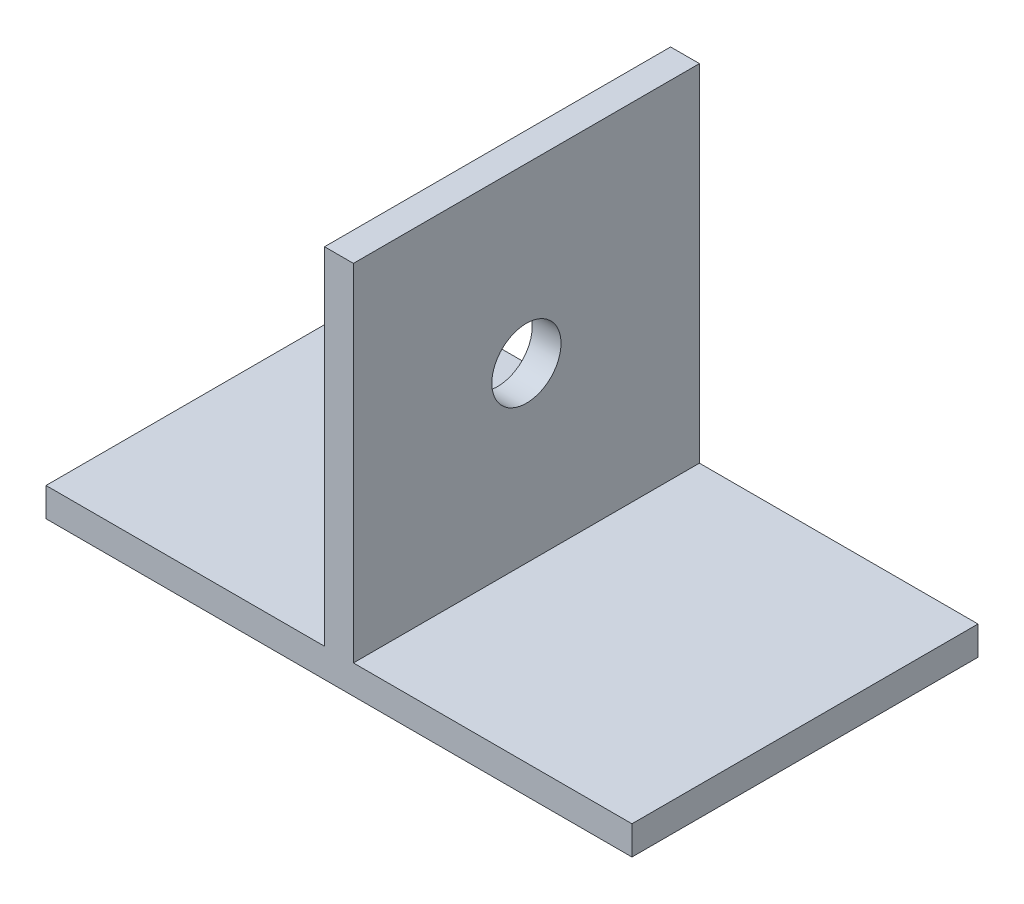
SolidWorks part; units mm, degrees
ref_plane "Front" through (0, 0, 0) normal (0, 0, 1) x (1, 0, 0)
ref_plane "Top" through (0, 0, 0) normal (0, 1, 0) x (1, 0, 0)
ref_plane "Right" through (0, 0, 0) normal (1, 0, 0) x (0, 0, -1)
sketch "草图1" plane through (0, 0, 0) normal (0, 0, 1) x (1, 0, 0)
  line L0 (0, 0) -> (0, -23.8891) construction
  line L1 (25.4, 0) -> (-25.4, 0)
  line L2 (-25.4, 0) -> (-25.4, 2.5)
  line L3 (-25.4, 2.5) -> (-1.25, 2.5)
  line L4 (-1.25, 2.5) -> (-1.25, 32.5)
  line L5 (-1.25, 32.5) -> (1.25, 32.5)
  line L6 (25.4, 0) -> (25.4, 2.5)
  line L7 (25.4, 2.5) -> (1.25, 2.5)
  line L8 (1.25, 2.5) -> (1.25, 32.5)
  point P8 (0, 32.5)
  point P12 (0, 0)
  dimension "D1" = 25.4
  dimension "D2" = 2.5
  dimension "D3" = 1.25
  dimension "D4" = 30
extrude "凸台-拉伸1" add sketch "草图1" along normal blind 30
sketch "草图2" plane through (1.25, 0, 0) normal (1, 0, 0) x (0, 0, -1)
  line L0 (-30, 2.5) -> (-30, 32.5) construction
  line L1 (-30, 32.5) -> (0, 32.5) construction
  circle A0 centre (-15, 17.5) radius 3
  dimension "D1" = 6
  dimension "D2" = 15
  dimension "D3" = 15
extrude "切除-拉伸1" cut sketch "草图2" against normal blind 50.8
